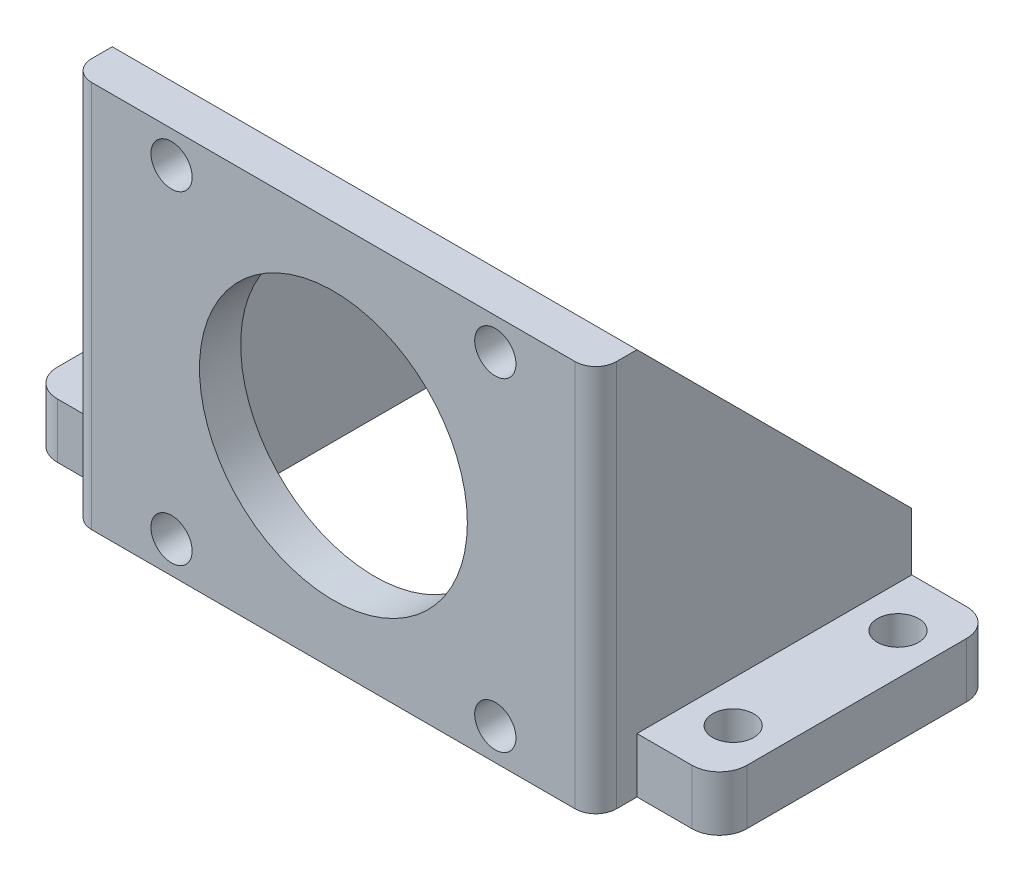
SolidWorks part; units mm, degrees
ref_plane "Front Plane" through (0, 0, 0) normal (0, 0, 1) x (1, 0, 0)
ref_plane "Top Plane" through (0, 0, 0) normal (0, 1, 0) x (1, 0, 0)
ref_plane "Right Plane" through (0, 0, 0) normal (1, 0, 0) x (0, 0, -1)
sketch "Sketch1" plane through (0, 0, 0) normal (0, 0, 1) x (1, 0, 0)
  line L1 (0, 0) -> (76.4, 0)
  line L2 (0, 0) -> (0, 56.4)
  line L3 (0, 56.4) -> (76.4, 56.4)
  line L4 (76.4, 0) -> (76.4, 56.4)
  circle A0 centre (38.2, 28.2) radius 19.5
  circle A1 centre (14.63, 51.77) radius 3
  circle A2 centre (61.77, 51.77) radius 3
  circle A3 centre (61.77, 4.63) radius 3
  circle A4 centre (14.63, 4.63) radius 3
  dimension "D3" = 28.2
  dimension "D4" = 38.2
  dimension "D5" = 39
  dimension "D6" = 6
  dimension "D7" = 6
  dimension "D8" = 6
  dimension "D9" = 6
  dimension "D10" = 47.14
  dimension "D11" = 47.14
  dimension "D12" = 47.14
  dimension "D13" = 47.14
  dimension "D14" = 4.63
  dimension "D15" = 4.63
  dimension "D16" = 23.57
  dimension "D17" = 23.57
  dimension "D1" = 56.4
  dimension "D2" = 76.4
extrude "Boss-Extrude1" add sketch "Sketch1" along normal blind 6
sketch "Sketch2" plane through (0, 0, 0) normal (0, 0, -1) x (-1, 0, 0)
  line L0 (-76.4, 56.4) -> (0, 56.4) construction
  line L1 (-76.4, 0) -> (-66.9, 0)
  line L2 (-76.4, 0) -> (-76.4, 56.4)
  line L3 (-76.4, 56.4) -> (-66.9, 56.4)
  line L4 (-66.9, 0) -> (-66.9, 56.4)
  line L6 (0, 0) -> (-9.5, 0)
  line L7 (0, 0) -> (0, 56.4)
  line L8 (0, 56.4) -> (-9.5, 56.4)
  line L9 (-9.5, 0) -> (-9.5, 56.4)
  dimension "D1" = 9.5
  dimension "D2" = 9.5
extrude "Boss-Extrude2" add sketch "Sketch2" along normal blind 40
fillet "Fillet1" radius 3 2 edges at (76.4, 28.2, 6) (0, 28.2, 6)
sketch "Sketch3" plane through (0, 0, 0) normal (-1, 0, 0) x (0, 0, 1)
  line L1 (-40, 0) -> (0, 0)
  line L2 (-40, 0) -> (-40, 8)
  line L3 (-40, 8) -> (0, 8)
  line L4 (0, 0) -> (0, 8)
  dimension "D1" = 8
extrude "Boss-Extrude3" add sketch "Sketch3" along normal blind 12
sketch "Sketch4" plane through (76.4, 0, 0) normal (1, 0, 0) x (0, 0, -1)
  line L0 (40, 56.4) -> (40, 0) construction
  line L1 (0, 0) -> (40, 0)
  line L2 (0, 0) -> (0, 8)
  line L3 (0, 8) -> (40, 8)
  line L4 (40, 0) -> (40, 8)
  dimension "D1" = 8
extrude "Boss-Extrude4" add sketch "Sketch4" along normal blind 12
fillet "Fillet2" radius 4 4 edges at (-12, 4, 0) (-12, 4, -40) (88.4, 4, -40) (88.4, 4, 0)
sketch "Sketch5" plane through (0, 8, 0) normal (0, 1, 0) x (1, 0, 0)
  line L0 (-12, 4) -> (-12, 36) construction
  line L1 (88.4, 36) -> (88.4, 4) construction
  line L2 (-8, 40) -> (0, 40) construction
  line L3 (-8, 0) -> (0, 0) construction
  circle A0 centre (-6, 32) radius 3
  circle A1 centre (-6, 8) radius 3
  circle A2 centre (82.4, 32) radius 3
  circle A3 centre (82.4, 8) radius 3
  dimension "D1" = 6
  dimension "D2" = 6
  dimension "D3" = 6
  dimension "D4" = 6
  dimension "D5" = 6
  dimension "D6" = 6
  dimension "D7" = 6
  dimension "D8" = 6
  dimension "D9" = 8
  dimension "D10" = 8
  dimension "D11" = 8
  dimension "D12" = 8
extrude "Cut-Extrude1" cut sketch "Sketch5" against normal blind 12
chamfer "Chamfer1" distance 40 angle 45 2 edges at (4.75, 56.4, -40) (71.65, 56.4, -40)
